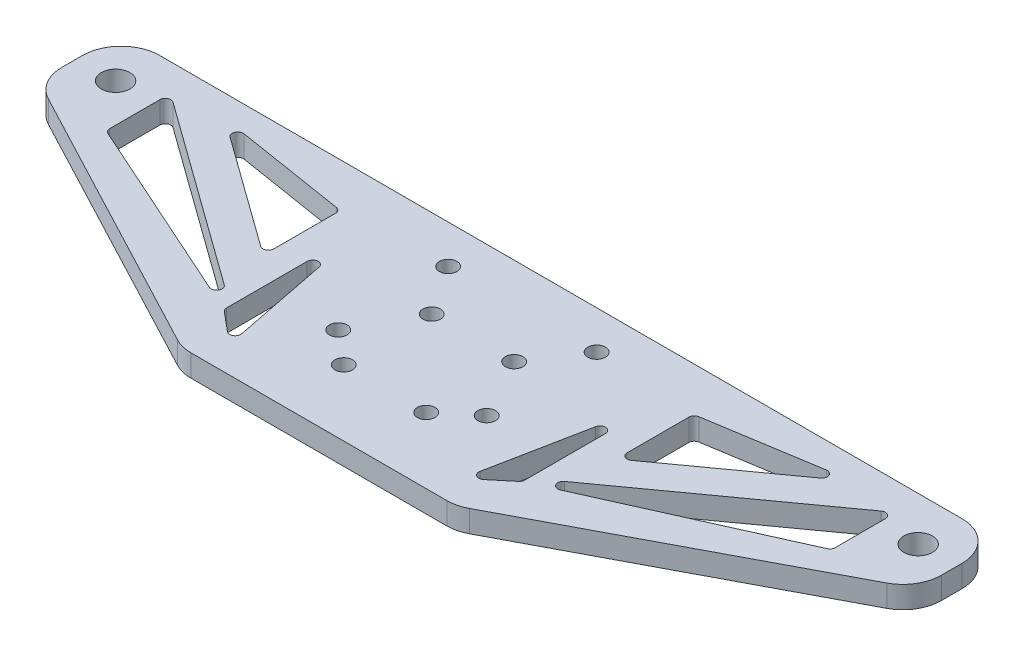
SolidWorks part; units mm, degrees
material "Thornel Mat VMA"
ref_plane "Front" through (0, 0, 0) normal (0, 0, 1) x (1, 0, 0)
ref_plane "Top" through (0, 0, 0) normal (0, 1, 0) x (1, 0, 0)
ref_plane "Right" through (0, 0, 0) normal (1, 0, 0) x (0, 0, -1)
sketch "草图1" plane through (0, 0, 0) normal (0, 1, 0) x (1, 0, 0)
  line L0 (0, 40.0348) -> (0, 0) construction
  line L1 (25, 0) -> (-25, 0)
  line L2 (-25, 0) -> (-80, 29)
  line L3 (-80, 29) -> (-80, 44)
  line L4 (-80, 44) -> (80, 44)
  line L5 (80, 29) -> (80, 44)
  line L6 (25, 0) -> (80, 29)
  point P9 (0, 44)
  dimension "D1" = 44
  dimension "D2" = 80
  dimension "D3" = 25
  dimension "D4" = 15
extrude "凸台-拉伸1" add sketch "草图1" along normal blind 4
sketch "草图2" plane through (0, 4, 0) normal (0, 1, 0) x (1, 0, 0)
  line L0 (0, 0) -> (0, 44) construction
  line L1 (80, 44) -> (-80, 44) construction
  line L2 (-7.5, 28) -> (-7.5, 12) construction
  line L3 (-7.5, 20) -> (7.5, 20) construction
  line L4 (7.5, 28) -> (7.5, 12) construction
  circle A0 centre (-7.5, 28) radius 1.6
  circle A3 centre (7.5, 28) radius 1.6
  circle A4 centre (-7.5, 12) radius 1.6
  circle A5 centre (7.5, 12) radius 1.6
  point P14 (0, 20)
  dimension "D1" = 3.2
  dimension "D2" = 16
  dimension "D4" = 16
  dimension "D3" = 7.5
extrude "切除-拉伸1" cut sketch "草图2" against normal through all
sketch "草图3" plane through (0, 4, 0) normal (0, 1, 0) x (1, 0, 0)
  line L0 (-80, 44) -> (-80, 29) construction
  line L1 (80, 44) -> (-80, 44) construction
  line L23 (-25, 0) -> (25, 0) construction
  line L24 (-66, 37.0459) -> (-66, 27.9182)
  line L25 (-65.4092, 27.0057) -> (-31.9468, 12.0011)
  line L26 (-30.9527, 13.7247) -> (-64.4151, 37.857)
  line L27 (-53.7123, 37.5359) -> (-33.714, 23.1136)
  line L28 (-32.129, 23.9247) -> (-32.129, 35.1473)
  line L29 (-32.971, 36.1347) -> (-52.9694, 39.3345)
  line L32 (-21.6763, 7.6101) -> (-25.148, 25.1763)
  line L33 (-80, 29) -> (-25, 0) construction
  line L34 (-13.5, 37) -> (-13.5, 17) construction
  line L35 (-27.129, 24.9824) -> (-27.129, 10.3092)
  line L36 (-26.7692, 9.541) -> (-23.2975, 6.6479)
  line L37 (-13.5, 37) -> (-7.5, 28) construction
  line L38 (-4.3247, 4.8409) -> (-21.129, 4.8409) construction
  line L39 (0, 30) -> (0, 0) construction
  line L40 (4.3247, 4.8409) -> (21.129, 4.8409) construction
  line L41 (7.5, 20.5) -> (7.5, 10.5) construction
  line L42 (26.7692, 9.541) -> (23.2975, 6.6479)
  line L43 (27.129, 24.9824) -> (27.129, 10.3092)
  line L44 (21.6763, 7.6101) -> (25.148, 25.1763)
  line L45 (32.971, 36.1347) -> (52.9694, 39.3345)
  line L46 (32.129, 23.9247) -> (32.129, 35.1473)
  line L47 (53.7123, 37.5359) -> (33.714, 23.1136)
  line L48 (30.9527, 13.7247) -> (64.4151, 37.857)
  line L49 (65.4092, 27.0057) -> (31.9468, 12.0011)
  line L50 (66, 37.0459) -> (66, 27.9182)
  line L51 (-7.5, 12) -> (-13.5, 17) construction
  circle A0 centre (-73, 36) radius 2.6
  arc A1 (-23.2975, 6.6479) -> (-21.6763, 7.6101) centre (-22.6573, 7.4162) ccw
  arc A2 (-27.129, 10.3092) -> (-26.7692, 9.541) centre (-26.129, 10.3092) ccw
  arc A3 (-27.129, 24.9824) -> (-25.148, 25.1763) centre (-26.129, 24.9824) cw
  arc A4 (-32.129, 35.1473) -> (-32.971, 36.1347) centre (-33.129, 35.1473) ccw
  arc A5 (-53.7123, 37.5359) -> (-52.9694, 39.3345) centre (-53.1274, 38.347) cw
  arc A6 (-33.714, 23.1136) -> (-32.129, 23.9247) centre (-33.129, 23.9247) ccw
  arc A7 (-30.9527, 13.7247) -> (-31.9468, 12.0011) centre (-31.5376, 12.9136) cw
  arc A8 (-66, 27.9182) -> (-65.4092, 27.0057) centre (-65, 27.9182) ccw
  arc A9 (-66, 37.0459) -> (-64.4151, 37.857) centre (-65, 37.0459) cw
  arc A10 (66, 37.0459) -> (64.4151, 37.857) centre (65, 37.0459) ccw
  arc A11 (66, 27.9182) -> (65.4092, 27.0057) centre (65, 27.9182) cw
  arc A12 (30.9527, 13.7247) -> (31.9468, 12.0011) centre (31.5376, 12.9136) ccw
  arc A13 (33.714, 23.1136) -> (32.129, 23.9247) centre (33.129, 23.9247) cw
  arc A14 (53.7123, 37.5359) -> (52.9694, 39.3345) centre (53.1274, 38.347) ccw
  arc A15 (32.129, 35.1473) -> (32.971, 36.1347) centre (33.129, 35.1473) cw
  arc A16 (27.129, 24.9824) -> (25.148, 25.1763) centre (26.129, 24.9824) ccw
  arc A17 (27.129, 10.3092) -> (26.7692, 9.541) centre (26.129, 10.3092) cw
  arc A18 (23.2975, 6.6479) -> (21.6763, 7.6101) centre (22.6573, 7.4162) cw
  circle A19 centre (73, 36) radius 2.6
  circle A20 centre (-13.5, 17) radius 1.6
  circle A21 centre (-13.5, 37) radius 1.6
  circle A22 centre (13.5, 17) radius 1.6
  circle A23 centre (13.5, 37) radius 1.6
  point P24 (-27.129, 9.8409)
  point P32 (-27.129, 35.2)
  point P35 (-32.129, 36)
  point P38 (-57.129, 40)
  point P43 (-23, 7.9894)
  point P46 (-66, 27.2707)
  point P49 (-66, 39)
  point P86 (66, 39)
  point P87 (66, 27.2707)
  point P88 (23, 7.9894)
  point P89 (57.129, 40)
  point P90 (32.129, 36)
  point P91 (27.129, 35.2)
  point P92 (27.129, 9.8409)
  dimension "D1" = 5.2
  dimension "D2" = 7
  dimension "D3" = 8
  dimension "D15" = 1
  dimension "D16" = 3.2
  dimension "D17" = 27
  dimension "D18" = 17
  dimension "D20" = 3.2
  dimension "D4" = 7
  dimension "D5" = 5
  dimension "D6" = 5
  dimension "D7" = 8
  dimension "D8" = 6
  dimension "D9" = 4
  dimension "D10" = 8
  dimension "D11" = 2
  dimension "D12" = 5
  dimension "D13" = 25
  dimension "D14" = 6
  dimension "D19" = 20
extrude "切除-拉伸2" cut sketch "草图3" against normal through all
fillet "圆角1" radius 7 6 edges at (-25, 2, 0) (25, 2, 0) (80, 2, -29) (80, 2, -44) (-80, 2, -29) (-80, 2, -44)
